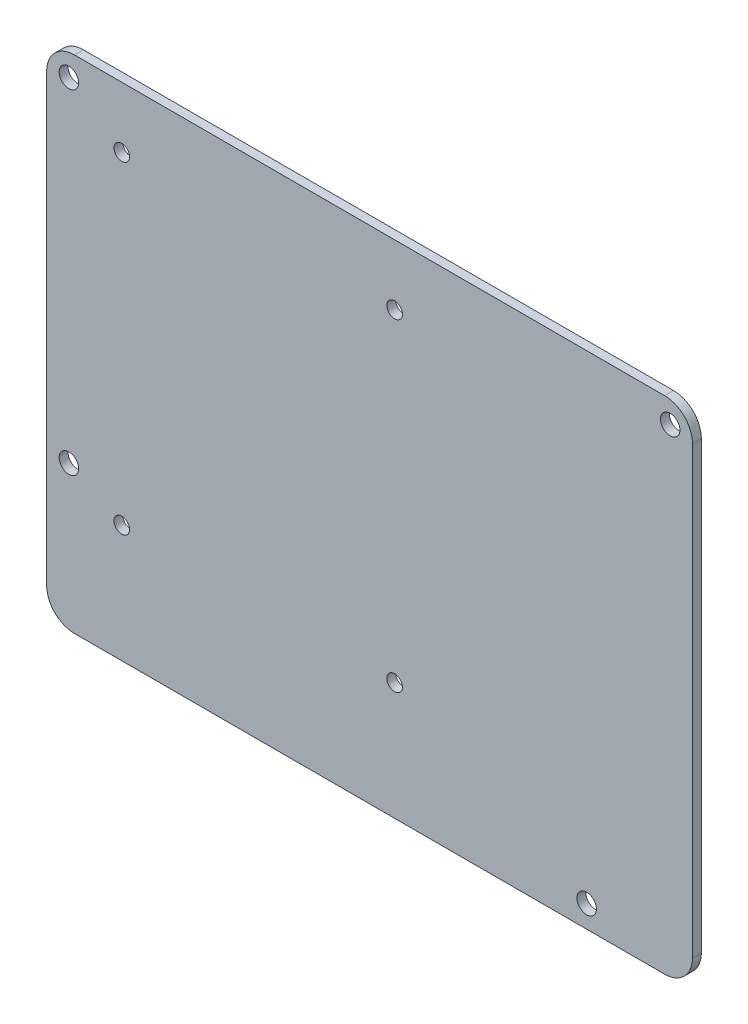
SolidWorks part; units mm, degrees
ref_plane "정면" through (0, 0, 0) normal (0, 0, 1) x (1, 0, 0)
ref_plane "윗면" through (0, 0, 0) normal (0, 1, 0) x (1, 0, 0)
ref_plane "우측면" through (0, 0, 0) normal (1, 0, 0) x (0, 0, -1)
sketch "Sketch1" plane through (0, 0, 0) normal (0, 0, 1) x (1, 0, 0)
  line L1 (19, 86) -> (-97, 86)
  line L2 (19, 86) -> (19, -4)
  line L3 (19, -4) -> (-97, -4)
  line L4 (-97, 86) -> (-97, -4)
  line L5 (19, 86) -> (-97, -4) construction
  line L6 (19, -4) -> (-97, 86) construction
  line L9 (-97, -4) -> (-97, 86) construction
  line L11 (19, -4) -> (-97, -4) construction
  point P0 (-39, 41)
  dimension "D1" = 116
  dimension "D2" = 90
extrude "Boss-Extrude1" add sketch "Sketch1" along normal blind 1.6
hole_wizard "Ø3.5 (3.5) Diameter Hole1" positions "Sketch3" profile "Sketch2" hole size "Ø3.5" standard "ANSI Metric" end condition through all
sketch "Sketch3" plane through (0, 0, 1.6) normal (0, 0, 1) x (1, 0, 0)
  line L0 (19, -4) -> (19, 86) construction
  line L1 (-97, -4) -> (19, -4) construction
  point P0 (0, 0)
  point P3 (15, 82)
  point P6 (-93, 82)
  point P9 (-93, 22)
  dimension "D1" = 4
  dimension "D2" = 19
  dimension "D3" = 4
  dimension "D4" = 26
  dimension "D5" = 112
  dimension "D6" = 112
  dimension "D7" = 86
  dimension "D8" = 86
sketch "Sketch2" plane through (0, 0, 1.6) normal (1, 0, 0) x (0, -1, 0)
  line L0 (0, 0) -> (0, 1.6)
  line L1 (0, 1.6) -> (1.75, 1.6)
  line L2 (1.75, 1.6) -> (1.75, 0)
  line L5 (1.75, 0) -> (0, 0)
  line L11 (0, -6.35) -> (0, 107.95) construction
  dimension "Thru Hole Dia." = 3.5
  dimension "Thru Hole Depth" = 1.6
fillet "Fillet1" radius 5 4 edges at (19, 86, 0.8) (-97, 86, 0.8) (-97, -4, 0.8) (19, -4, 0.8)
hole_wizard "Ø2.8 (2.8) Diameter Hole1" positions "Sketch5" profile "Sketch4" hole size "Ø2.8" standard "ANSI Metric" end condition through all
sketch "Sketch5" plane through (0, 0, 0) normal (0, 0, -1) x (-1, 0, 0)
  line L2 (-19, 1) -> (-19, 81) construction
  line L3 (-14, 86) -> (92, 86) construction
  line L4 (92, -4) -> (-14, -4) construction
  point P0 (34.5, 75.1)
  point P3 (83.5, 75.1)
  point P6 (83.5, 17.1)
  point P9 (34.5, 17.1)
  dimension "D1" = 53.5
  dimension "D2" = 53.5
  dimension "D3" = 10.9
  dimension "D4" = 68.9
  dimension "D5" = 21.1
  dimension "D6" = 79.1
  dimension "D7" = 102.5
  dimension "D8" = 102.5
  dimension "D9" = 21.1
  dimension "D10" = 79.1
sketch "Sketch4" plane through (-34.5, 75.1, 0) normal (1, 0, 0) x (0, 1, 0)
  line L0 (0, 0) -> (0, 1.6)
  line L1 (0, 1.6) -> (1.4, 1.6)
  line L2 (1.4, 1.6) -> (1.4, 0)
  line L5 (1.4, 0) -> (0, 0)
  line L11 (0, -6.35) -> (0, 107.95) construction
  dimension "Thru Hole Dia." = 2.8
  dimension "Thru Hole Depth" = 1.6
ref_plane "Plane1" through (14, 86, 0) normal (-1, 0, 0) x (0, 0, 1)
sketch "Sketch6" plane through (14, 86, 0) normal (-1, 0, 0) x (0, 0, 1)
sketch "Sketch7" [suppressed] plane through (0, 0, 0) normal (0, 0, -1) x (-1, 0, 0)
  line L0 (83.5, 75.1) -> (83.5, 17.1) construction
  line L1 (71.0421, 46.1) -> (102.279, 46.1) construction
  line L3 (92, -4) -> (-14, -4) construction
  line L4 (-19, 1) -> (-19, 81) construction
  dimension "D1" = 50.1
  dimension "D2" = 102.5
